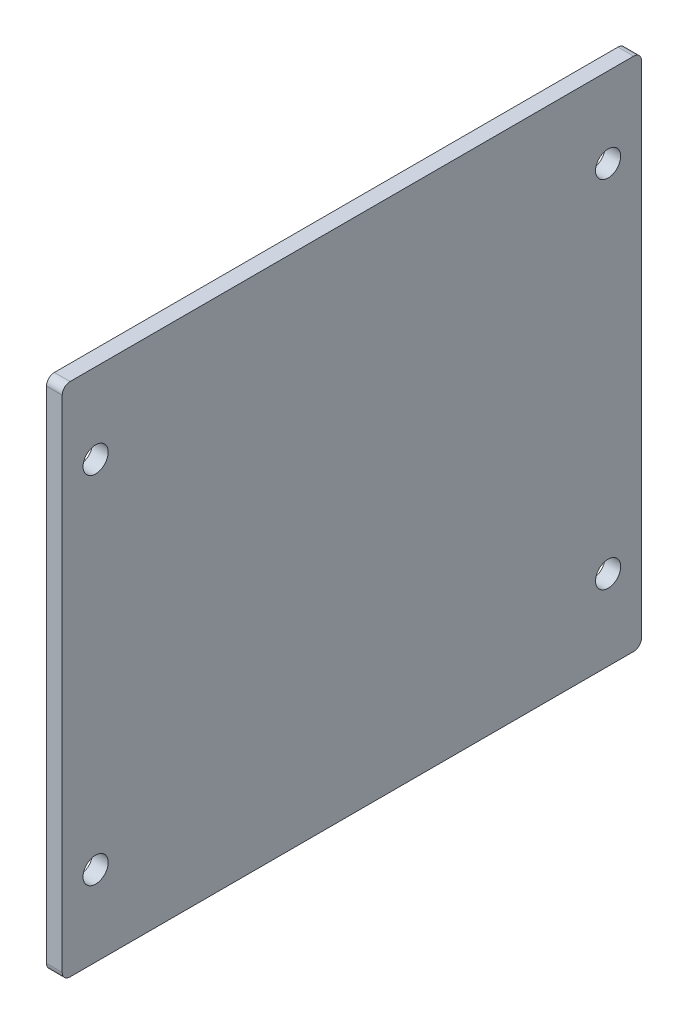
SolidWorks part; units mm, degrees
ref_plane "Front Plane" through (0, 0, 0) normal (0, 0, 1) x (1, 0, 0)
ref_plane "Top Plane" through (0, 0, 0) normal (0, 1, 0) x (1, 0, 0)
ref_plane "Right Plane" through (0, 0, 0) normal (1, 0, 0) x (0, 0, -1)
sketch "Sketch1" plane through (0, 0, 0) normal (1, 0, 0) x (0, 0, -1)
  line L1 (-36.85, -79.8) -> (36.85, -79.8)
  line L2 (-36.85, -79.8) -> (-36.85, -14.2)
  line L3 (-36.85, -14.2) -> (36.85, -14.2)
  line L4 (36.85, -79.8) -> (36.85, -14.2)
  point P7 (-62.0156, -72.7344)
  dimension "D1" = 36.85
  dimension "D2" = 36.85
  dimension "D3" = 14.2
  dimension "D4" = 79.8
extrude "Boss-Extrude1" add sketch "Sketch1" along normal blind 2
fillet "Fillet1" radius 1 4 edges at (1, -79.8, 36.85) (1, -79.8, -36.85) (1, -14.2, -36.85) (1, -14.2, 36.85)
sketch "Sketch2" plane through (0, 0, 0) normal (1, 0, 0) x (0, 0, -1)
  line L0 (0, -14.2) -> (0, -79.8) construction
  line L1 (35.85, -14.2) -> (-35.85, -14.2) construction
  line L2 (-35.85, -79.8) -> (35.85, -79.8) construction
  line L3 (-36.85, -47) -> (36.85, -47) construction
  line L4 (-36.85, -15.2) -> (-36.85, -78.8) construction
  line L5 (36.85, -78.8) -> (36.85, -15.2) construction
  line L6 (1.1, 0) -> (-1.1, 0) construction
  circle A0 centre (-32.6, -69.6) radius 1.6
  circle A1 centre (32.6, -69.6) radius 1.6
  circle A2 centre (-32.6, -69.6) radius 1.6
  circle A3 centre (32.6, -69.6) radius 1.6
  circle A4 centre (32.6, -24.4) radius 1.6
  circle A5 centre (-32.6, -24.4) radius 1.6
  circle A6 centre (32.6, -24.4) radius 1.6
  circle A7 centre (-32.6, -24.4) radius 1.6
  point P14 (0, 0)
  point P15 (0, 0)
  point P16 (0, 0)
  point P19 (0, 0)
  point P30 (0, 0)
  dimension "D2" = 3.2
  dimension "D1" = 32.6
  dimension "D3" = 69.6
extrude "Cut-Extrude1" cut sketch "Sketch2" along normal through all both and the other way through all contours A4 | A5 | A1 | A0
